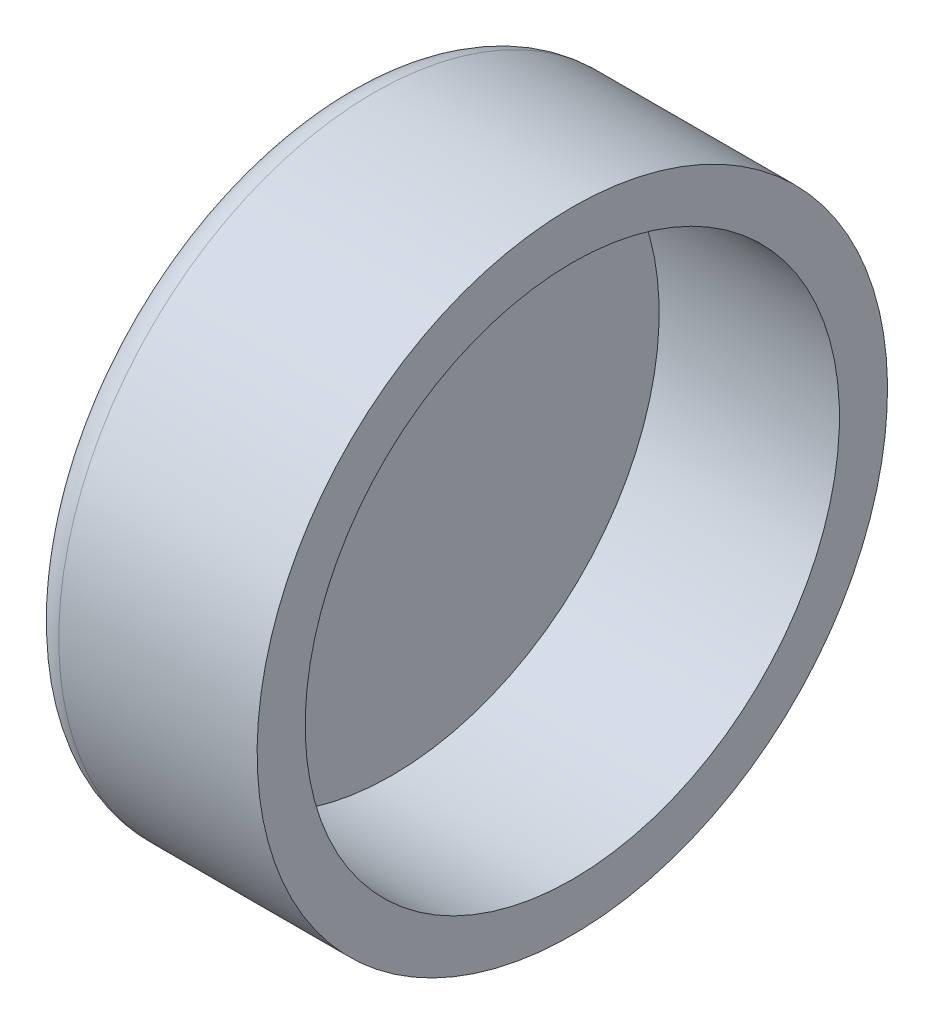
SolidWorks part; units mm, degrees
ref_plane "Front" through (0, 0, 0) normal (0, 0, 1) x (1, 0, 0)
ref_plane "Top" through (0, 0, 0) normal (0, 1, 0) x (1, 0, 0)
ref_plane "Right" through (0, 0, 0) normal (1, 0, 0) x (0, 0, -1)
sketch "Croquis2" plane through (0, 0, 0) normal (0, 0, 1) x (1, 0, 0)
  line L0 (0, 44.45) -> (-30, 44.45)
  line L1 (-30, 44.45) -> (-30, 0)
  line L2 (-30, 0) -> (-38, 0)
  line L3 (0, 44.45) -> (0, 52.45)
  line L5 (0, 52.45) -> (-38, 52.45)
  line L6 (-38, 52.45) -> (-38, 0)
  dimension "D1" = 44.45
  dimension "D2" = 30
  dimension "D3" = 8
  dimension "D4" = 8
revolve "Revolución1" add sketch "Croquis2" angle 360 about L2
fillet "Redondeo1" radius 5 1 edges at (-38, 52.45, 0)
